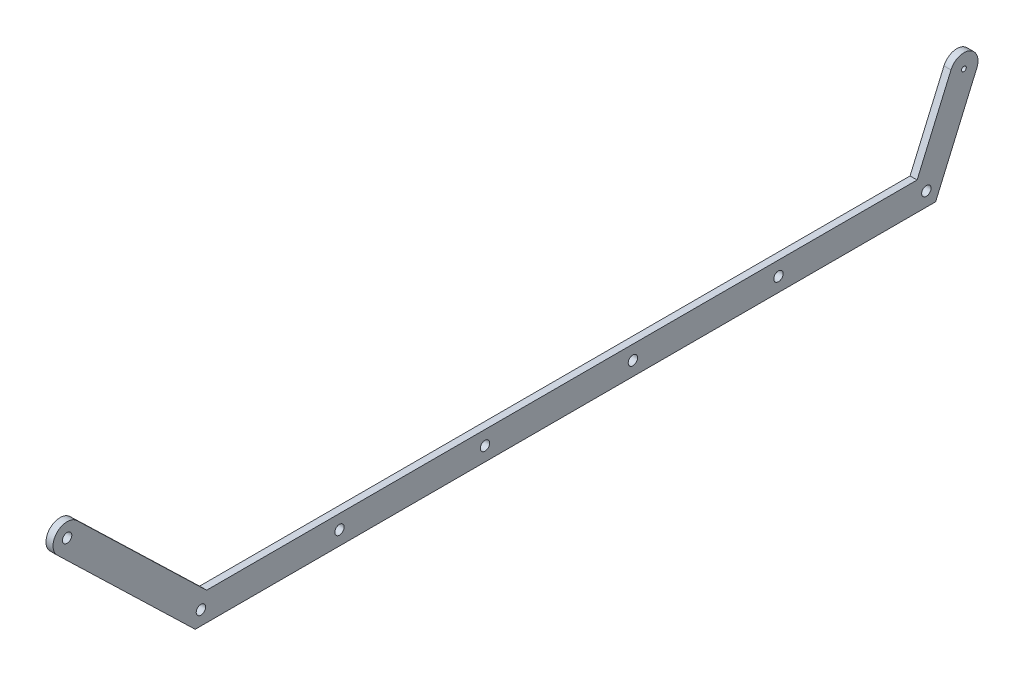
SolidWorks part; units mm, degrees
ref_plane "Front Plane" through (0, 0, 0) normal (0, 0, 1) x (1, 0, 0)
ref_plane "Top Plane" through (0, 0, 0) normal (0, 1, 0) x (1, 0, 0)
ref_plane "Right Plane" through (0, 0, 0) normal (1, 0, 0) x (0, 0, -1)
sketch "Sketch1" plane through (0, 0, 0) normal (1, 0, 0) x (0, 0, -1)
  line L0 (57, -55) -> (366, -55) construction
  line L1 (57, -55) -> (0, 0) construction
  line L2 (366, -55) -> (382, -18) construction
  line L3 (0, 0) -> (4.1662, 4.3177) construction
  line L4 (4.1662, 4.3177) -> (-4.1662, -4.3177) construction
  line L5 (57, -55) -> (61.1662, -50.6823) construction
  line L6 (61.1662, -50.6823) -> (52.8338, -59.3177) construction
  line L7 (57, -55) -> (57, -61) construction
  line L8 (57, -61) -> (57, -49) construction
  line L9 (366, -55) -> (366, -49) construction
  line L10 (366, -49) -> (366, -61) construction
  line L11 (366, -55) -> (360.4929, -52.6185) construction
  line L12 (360.4929, -52.6185) -> (371.5071, -57.3815) construction
  line L13 (382, -18) -> (376.4929, -15.6185) construction
  line L14 (376.4929, -15.6185) -> (387.5071, -20.3815) construction
  line L15 (376.4929, -15.6185) -> (360.4929, -52.6185) construction
  line L16 (371.5071, -57.3815) -> (387.5071, -20.3815) construction
  line L17 (366, -49) -> (57, -49) construction
  line L18 (57, -61) -> (366, -61) construction
  line L19 (366, -61) -> (371.5071, -57.3815) construction
  line L20 (52.8338, -59.3177) -> (57, -61) construction
  line L21 (52.8338, -59.3177) -> (-4.1662, -4.3177) construction
  line L22 (4.1662, 4.3177) -> (61.1662, -50.6823) construction
  line L23 (59.4228, -49) -> (4.1662, 4.3177)
  line L24 (-4.1662, -4.3177) -> (54.5612, -61)
  line L25 (54.5612, -61) -> (366, -61)
  line L26 (366, -61) -> (386.2207, -61) construction
  line L27 (387.5071, -20.3815) -> (371.5071, -57.3815) construction
  line L28 (371.5071, -57.3815) -> (366.2352, -69.5729) construction
  line L29 (366, -61) -> (369.9424, -61)
  line L30 (369.9424, -61) -> (387.5071, -20.3815)
  line L31 (376.4929, -15.6185) -> (362.0576, -49)
  line L32 (362.0576, -49) -> (59.4228, -49)
  circle A0 centre (0, 0) radius 2
  circle A1 centre (57, -55) radius 2
  circle A2 centre (116, -55) radius 2
  circle A3 centre (178, -55) radius 2
  circle A4 centre (241, -55) radius 2
  circle A5 centre (303, -55) radius 2
  circle A6 centre (366, -55) radius 2
  circle A7 centre (382, -18) radius 1
  arc A8 (-4.1662, -4.3177) -> (4.1662, 4.3177) centre (0, 0) cw
  arc A9 (376.4929, -15.6185) -> (387.5071, -20.3815) centre (382, -18) cw
  point P17 (59.4228, -49)
  point P20 (0, 0)
  point P32 (54.5612, -61)
  point P36 (369.9424, -61)
  point P38 (362.0576, -49)
  dimension "D1" = 4
  dimension "D2" = 4
  dimension "D7" = 4
  dimension "D9" = 62
  dimension "D10" = 4
  dimension "D11" = 4
  dimension "D13" = 4
  dimension "D15" = 4
  dimension "D17" = 2
  dimension "D38" = 6
  dimension "D40" = 6
  dimension "D3" = 57
  dimension "D4" = 55
  dimension "D5" = 79.2086
  dimension "D6" = 309
  dimension "D8" = 59
  dimension "D12" = 63
  dimension "D14" = 62
  dimension "D16" = 63
  dimension "D18" = 16
  dimension "D19" = 37
  dimension "D20" = 40.3113
  dimension "D21" = 90
  dimension "D22" = 90
  dimension "D23" = 90
  dimension "D24" = 90
  dimension "D25" = 6
  dimension "D26" = 6
  dimension "D27" = 12
  dimension "D28" = 12
  dimension "D29" = 6
  dimension "D30" = 12
  dimension "D31" = 6
  dimension "D32" = 12
  dimension "D33" = 6
  dimension "D34" = 12
  dimension "D35" = 6
  dimension "D36" = 12
  dimension "D37" = 81.6198
  dimension "D39" = 36.3689
extrude "Boss-Extrude1" add sketch "Sketch1" along normal blind 3 contours A9 L31 L32 L23 A8 L24 L25 L29 L30 A7 A6 A5 A4 A3 A2 A1 A0
